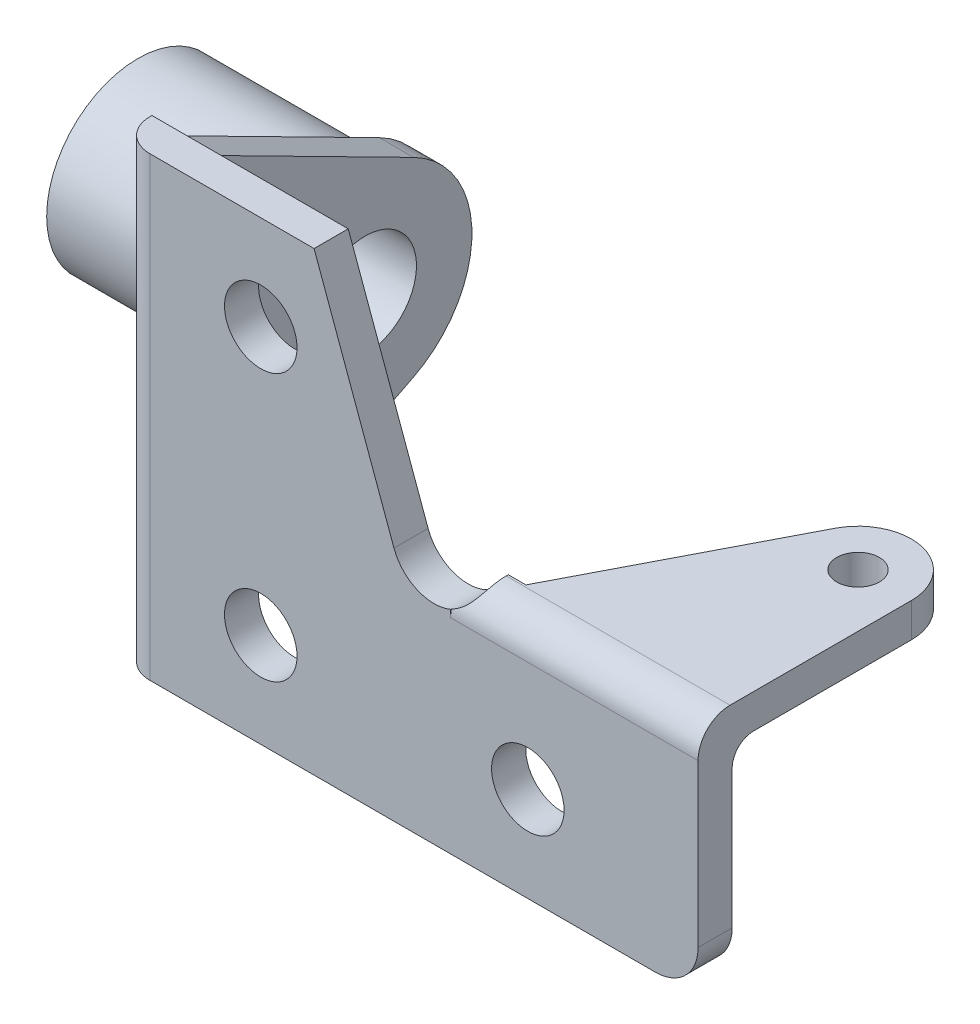
SolidWorks part; units mm, degrees
ref_plane "Front Plane" through (0, 0, 0) normal (0, 0, 1) x (1, 0, 0)
ref_plane "Top Plane" through (0, 0, 0) normal (0, 1, 0) x (1, 0, 0)
ref_plane "Right Plane" through (0, 0, 0) normal (1, 0, 0) x (0, 0, -1)
sketch "Sketch1" plane through (0, 0, 0) normal (0, 0, 1) x (1, 0, 0)
  line L0 (0, 0) -> (0, 27.1526)
  line L1 (0, 27.1526) -> (11.684, 27.1526)
  line L2 (11.684, 27.1526) -> (16.4405, 14.0843)
  line L3 (21.2141, 14.0843) -> (34.544, 14.0843)
  line L4 (34.544, 14.0843) -> (34.544, 0)
  line L5 (34.544, 0) -> (0, 0)
  line L6 (8.509, 21.5265) -> (8.509, 5.6261) construction
  line L7 (8.509, 5.6261) -> (24.4094, 5.6261) construction
  line L8 (8.509, 13.5763) -> (0, 13.5763) construction
  line L9 (18.8273, 14.953) -> (18.8273, 12.413) construction
  circle A0 centre (8.509, 21.5265) radius 2.159
  circle A1 centre (8.509, 5.6261) radius 2.159
  circle A2 centre (24.4094, 5.6261) radius 2.159
  arc A3 (16.4405, 14.0843) -> (21.2141, 14.0843) centre (18.8273, 14.953) ccw
  point P16 (18.8273, 12.413)
  dimension "D1" = 4.318
  dimension "D8" = 5.08
  dimension "D2" = 1.016
  dimension "D3" = 34.544
  dimension "D4" = 27.1526
  dimension "D5" = 8.509
  dimension "D6" = 11.684
  dimension "D7" = 15.9004
  dimension "D9" = 110
extrude "Boss-Extrude1" add sketch "Sketch1" along normal blind 2.032
sketch "Sketch2" plane through (0, 0, 0) normal (-1, 0, 0) x (0, 0, 1)
  line L0 (2.032, 0) -> (-13.5447, 7.9153)
  line L1 (2.032, 27.1526) -> (2.032, 0) construction
  line L2 (-13.5447, 19.2373) -> (2.032, 27.1526)
  line L3 (2.032, 0) -> (2.032, 27.1526)
  arc A0 (-13.5447, 19.2373) -> (-13.5447, 7.9153) centre (-10.668, 13.5763) ccw
  dimension "D2" = 6.35
  dimension "D1" = 12.7
extrude "Boss-Extrude2" add sketch "Sketch2" against normal blind 2.032
sketch "Sketch3" plane through (0, 0, 0) normal (-1, 0, 0) x (0, 0, 1)
  circle A0 centre (-10.668, 13.5763) radius 5.4356
  dimension "D1" = 10.8712
extrude "Boss-Extrude3" add sketch "Sketch3" along normal blind 11.5
sketch "Sketch4" plane through (-11.5, 0, 0) normal (-1, 0, 0) x (0, 0, 1)
  circle A0 centre (-10.668, 13.5763) radius 3.048
  dimension "D1" = 6.096
extrude "Cut-Extrude1" cut sketch "Sketch4" against normal through all
sketch "Sketch5" plane through (0, 14.0843, 0) normal (0, 1, 0) x (1, 0, 0)
  line L0 (21.2141, -2.032) -> (28.5498, 12.1285)
  line L1 (34.544, -2.032) -> (21.2141, -2.032) construction
  line L2 (34.544, 10.668) -> (34.544, -2.032)
  line L3 (34.544, -2.032) -> (21.2141, -2.032)
  arc A0 (34.544, 10.668) -> (28.5498, 12.1285) centre (31.369, 10.668) ccw
  circle A1 centre (31.369, 10.668) radius 1.27
  dimension "D1" = 3.175
  dimension "D3" = 2.54
  dimension "D2" = 12.7
extrude "Boss-Extrude4" add sketch "Sketch5" against normal blind 2.032
sketch "Sketch6" plane through (34.544, 0, 0) normal (1, 0, 0) x (0, 0, -1)
  line L0 (-2.032, 0) -> (-2.032, 14.0843) construction
  line L1 (-2.032, 14.0843) -> (10.668, 14.0843) construction
  line L2 (-0.127, 14.0843) -> (-2.032, 14.0843)
  line L3 (-2.032, 14.0843) -> (-2.032, 12.1793)
  arc A0 (-0.127, 14.0843) -> (-2.032, 12.1793) centre (-0.127, 12.1793) ccw
  dimension "D1" = 3.81
extrude "Cut-Extrude2" cut sketch "Sketch6" against normal blind 14.732
fillet "Fillet4" radius 1.905 1 edges at (0, 13.5763, 2.032)
fillet "Fillet5" radius 1.27 2 edges at (2.032, 13.5763, 0) (28.4054, 12.0523, 0)
fillet "Fillet6" radius 2.54 1 edges at (34.544, 0, 1.016)
